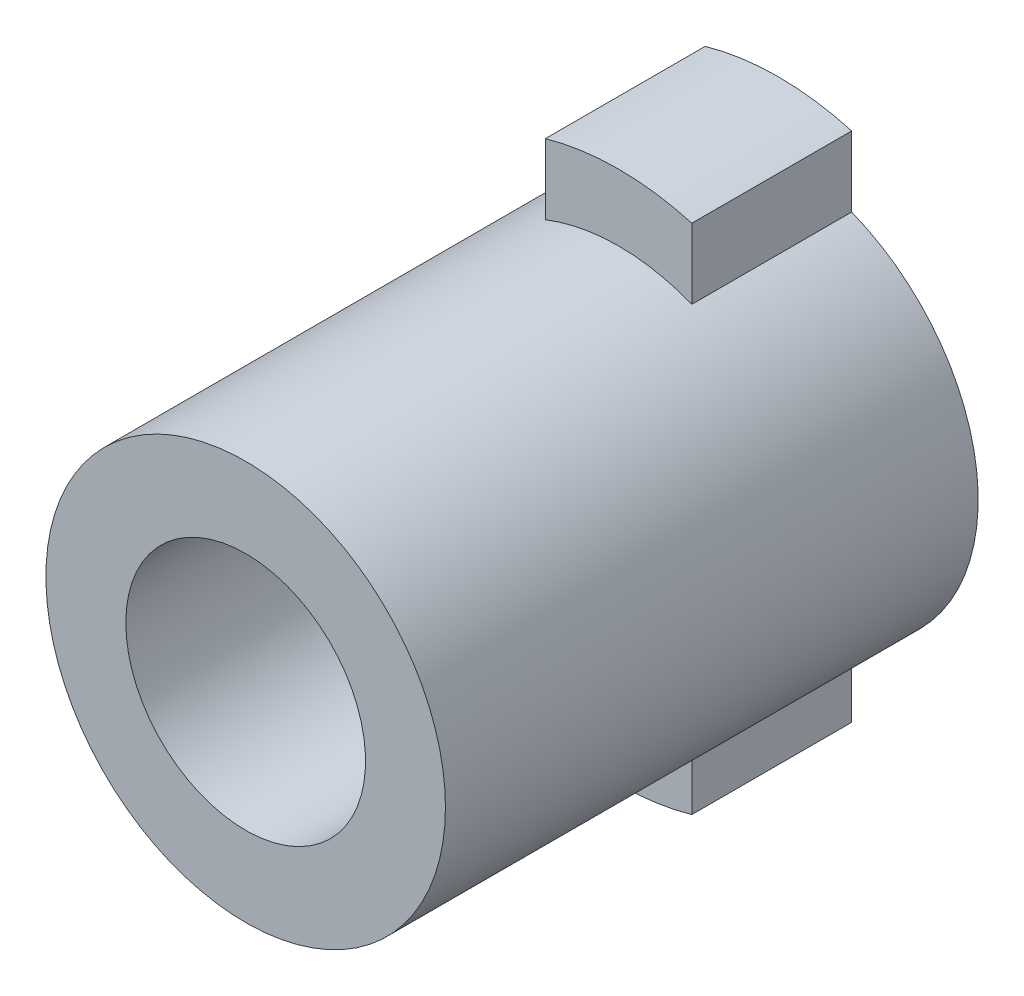
SolidWorks part; units mm, degrees
ref_plane "Top Plane" through (0, 0, 0) normal (0, 0, 1) x (1, 0, 0)
ref_plane "Right Plane" through (0, 0, 0) normal (0, 1, 0) x (1, 0, 0)
ref_plane "Front Plane" through (0, 0, 0) normal (1, 0, 0) x (0, 0, -1)
sketch "Sketch1" plane through (0, 0, 0) normal (0, 0, 1) x (1, 0, 0)
  circle A0 centre (0, 0) radius 7.5
  dimension "D1" = 15
extrude "Boss-Extrude1" add sketch "Sketch1" along normal blind 20
sketch "Sketch2" plane through (0, 0, 0) normal (0, 0, -1) x (-1, 0, 0)
  line L1 (2.75, -9.6144) -> (-2.75, -9.6144) construction
  line L2 (2.75, -9.6144) -> (2.75, 9.6144)
  line L3 (2.75, 9.6144) -> (-2.75, 9.6144) construction
  line L4 (-2.75, -9.6144) -> (-2.75, 9.6144)
  circle A0 centre (0, 0) radius 10 construction
  circle A1 centre (0, 0) radius 7.5 construction
  arc A2 (2.75, -9.6144) -> (-2.75, -9.6144) centre (0, 0) cw
  arc A3 (2.75, 9.6144) -> (-2.75, 9.6144) centre (0, 0) ccw
  dimension "D1" = 2.5
  dimension "D2" = 5.5
extrude "Boss-Extrude2" add sketch "Sketch2" against normal blind 6
sketch "Sketch3" plane through (0, 0, 0) normal (0, 0, -1) x (-1, 0, 0)
  circle A0 centre (0, 0) radius 4.5
  dimension "D1" = 9
extrude "Cut-Extrude1" cut sketch "Sketch3" against normal through all
